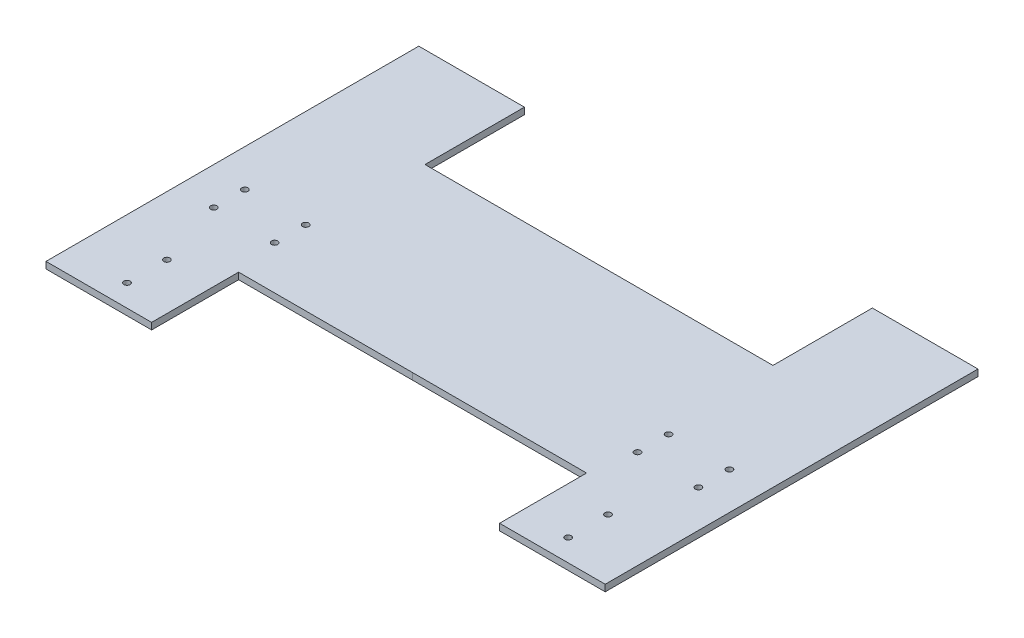
SolidWorks part; units mm, degrees
ref_plane "Front Plane" through (0, 0, 0) normal (0, 0, 1) x (1, 0, 0)
ref_plane "Top Plane" through (0, 0, 0) normal (0, 1, 0) x (1, 0, 0)
ref_plane "Right Plane" through (0, 0, 0) normal (1, 0, 0) x (0, 0, -1)
sketch "Sketch2" plane through (0, 0, 0) normal (0, 1, 0) x (1, 0, 0)
  line L1 (-225, -150) -> (225, -150)
  line L2 (-225, -150) -> (-225, 150)
  line L3 (-225, 150) -> (225, 150)
  line L4 (225, -150) -> (225, 150)
  line L5 (-225, -150) -> (225, 150) construction
  line L6 (-225, 150) -> (225, -150) construction
  point P0 (0, 0)
  dimension "D1" = 300
  dimension "D2" = 450
extrude "Base" add sketch "Sketch2" along normal blind 5.314
hole_wizard "Tap Drill for M6x1.0 rack bolts" positions "Sketch6" profile "Sketch4" hole size "M6x1.0" standard "ANSI Metric" end condition up to next
sketch "Sketch6" plane through (0, 5.314, 0) normal (0, 1, 0) x (1, 0, 0)
  line L0 (-225, 150) -> (-225, -150) construction
  line L1 (225, -150) -> (225, 150) construction
  line L2 (225, 150) -> (-225, 150) construction
  point P0 (-195, -45)
  point P2 (-146, -45)
  point P4 (-146, -20)
  point P6 (-195, -20)
  point P8 (146, -20)
  point P10 (195, -20)
  point P12 (195, -45)
  point P14 (146, -45)
  dimension "D1" = 49
  dimension "D2" = 25
  dimension "D3" = 30
  dimension "D4" = 30
  dimension "D5" = 49
  dimension "D6" = 170
sketch "Sketch4" plane through (-195, 5.314, 45) normal (1, 0, 0) x (0, 0, 1)
  line L0 (0, 0) -> (0, 5.314)
  line L1 (0, 5.314) -> (2.5, 5.314)
  line L2 (2.5, 5.314) -> (2.5, 0)
  line L5 (2.5, 0) -> (0, 0)
  line L11 (0, -6.35) -> (0, 107.95) construction
  dimension "Thru Hole Dia." = 5
  dimension "Thru Hole Depth" = 5.314
sketch "Sketch7" plane through (0, 5.314, 0) normal (0, 1, 0) x (1, 0, 0)
  line L0 (0, 0) -> (0, -80) construction
  line L1 (0, -80) -> (140, -80)
  line L2 (140, -80) -> (140, -150)
  line L3 (0, -80) -> (-140, -80)
  line L4 (-140, -80) -> (-140, -150)
  line L5 (-225, -150) -> (225, -150) construction
  dimension "D1" = 140
  dimension "D2" = 140
  dimension "D4" = 80
extrude "back cut" cut sketch "Sketch7" against normal through all
hole_wizard "Tap Drill for M6x1.0 motor bolts" positions "Sketch9" profile "Sketch8" hole size "M6x1.0" standard "ANSI Metric" end condition up to next
sketch "Sketch9" plane through (0, 5.314, 0) normal (0, 1, 0) x (1, 0, 0)
  line L0 (-225, 150) -> (-225, -150) construction
  line L1 (225, -150) -> (225, 150) construction
  point P0 (-177.5, -100.2526)
  point P2 (-177.5, -132.3414)
  point P4 (177.5, -100.2526)
  point P6 (177.5, -132.3414)
  dimension "D1" = 47.5
  dimension "D2" = 47.5
sketch "Sketch8" plane through (-177.5, 5.314, 100.2526) normal (1, 0, 0) x (0, 0, 1)
  line L0 (0, 0) -> (0, 5.314)
  line L1 (0, 5.314) -> (2.5, 5.314)
  line L2 (2.5, 5.314) -> (2.5, 0)
  line L5 (2.5, 0) -> (0, 0)
  line L11 (0, -6.35) -> (0, 107.95) construction
  dimension "Thru Hole Dia." = 5
  dimension "Thru Hole Depth" = 5.314
sketch "Sketch10" plane through (0, 5.314, 0) normal (0, 1, 0) x (1, 0, 0)
  line L0 (-140, -80) -> (-140, -150) construction
  line L1 (225, 150) -> (-225, 150) construction
  line L3 (-140, 150) -> (-140, 70)
  line L4 (-140, 70) -> (140, 70)
  line L5 (140, 70) -> (140, 150)
  line L6 (140, 150) -> (-140, 150)
  line L7 (140, -150) -> (140, -80) construction
  dimension "D1" = 80
extrude "Front cut" cut sketch "Sketch10" against normal through all
ref_plane "Plane2" through (-192.5, 0, 0) normal (-1, 0, 0) x (0, 0, 1)
ref_plane "Plane3" through (-148.5, 0, 0) normal (1, 0, 0) x (0, 0, -1)
ref_plane "Plane5" through (0, 0, 42.5) normal (0, 0, 1) x (1, 0, 0)
ref_plane "Plane6" through (0, 0, 22.5) normal (0, 0, -1) x (-1, 0, 0)
ref_plane "Plane7" through (0, 0, 22.5) normal (0, 0, -1) x (-1, 0, 0)
ref_plane "Plane8" through (0, 0, 42.5) normal (0, 0, 1) x (1, 0, 0)
ref_plane "Plane9" through (192.5, 0, 0) normal (1, 0, 0) x (0, 0, -1)
ref_plane "Plane10" through (148.5, 0, 0) normal (-1, 0, 0) x (0, 0, 1)
equation "\"width\"=300"
equation "\"D1@Sketch2\"=\"width\""
equation "\"D2@Sketch2\"=\"width\"+150"
equation "\"gauge3\"=10"
equation "\"gauge5\"=5.314"
equation "\"D1@Base\"=\"gauge5\""
